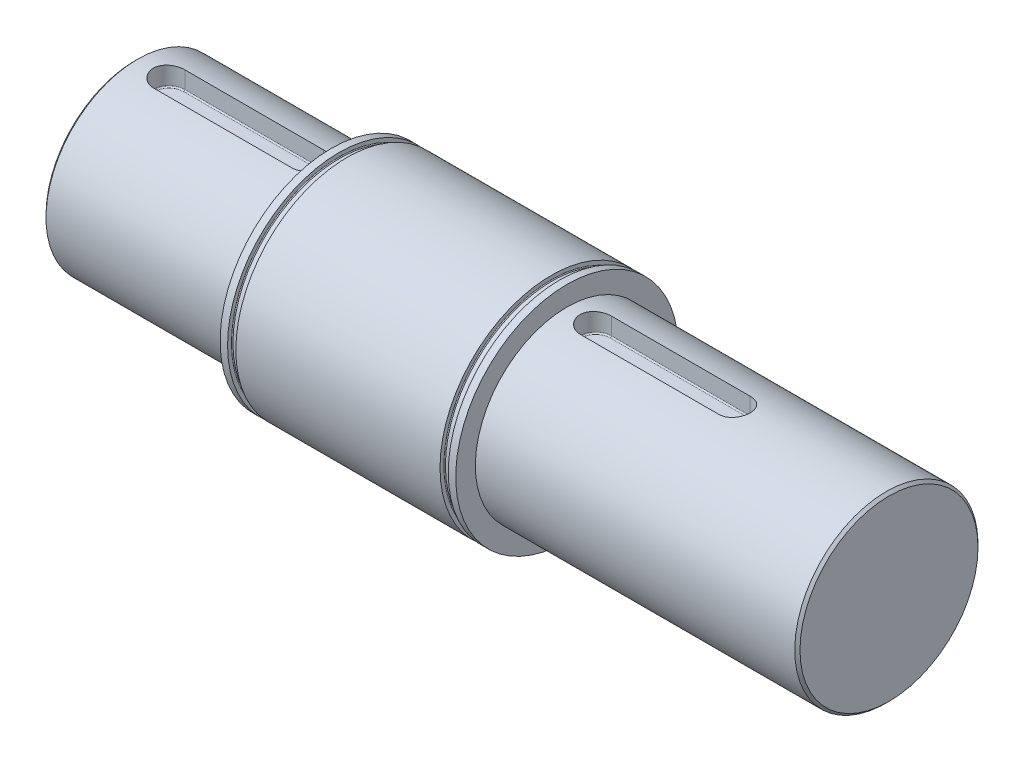
SolidWorks part; units mm, degrees
ref_plane "Front Plane" through (0, 0, 0) normal (0, 0, 1) x (1, 0, 0)
ref_plane "Top Plane" through (0, 0, 0) normal (0, 1, 0) x (1, 0, 0)
ref_plane "Right Plane" through (0, 0, 0) normal (1, 0, 0) x (0, 0, -1)
sketch "Sketch1" plane through (0, 0, 0) normal (0, 0, 1) x (1, 0, 0)
  line L0 (144, 0) -> (-144, 0) construction
  line L5 (144, 0) -> (144, 35)
  line L6 (144, 35) -> (21, 35)
  line L7 (21, 35) -> (21, 42.5)
  line L8 (21, 42.5) -> (-69, 42.5)
  line L12 (-144, 0) -> (144, 0)
  line L13 (-69, 42.5) -> (-69, 35)
  line L14 (-69, 35) -> (-144, 35)
  line L15 (-144, 35) -> (-144, 0)
  point P4 (0, 0)
  dimension "D1" = 123
  dimension "D2" = 90
  dimension "D3" = 35
  dimension "D4" = 42.5
  dimension "D5" = 75
revolve "Revolve1" add sketch "Sketch1" angle 360 about L0
sketch "Sketch3" plane through (0, 0, 0) normal (0, 0, 1) x (1, 0, 0)
  line L6 (9.2715, 0) -> (23.2848, 0) construction
  line L15 (21, 42.5) -> (-69, 42.5) construction
  line L16 (-66.15, 42.5) -> (-63, 42.5)
  line L17 (-66.15, 42.5) -> (-66.15, 40.75)
  line L18 (-66.15, 40.75) -> (-63, 40.75)
  line L19 (-63, 42.5) -> (-63, 40.75)
  line L20 (15, 42.5) -> (18.15, 42.5)
  line L21 (15, 42.5) -> (15, 40.75)
  line L22 (15, 40.75) -> (18.15, 40.75)
  line L23 (18.15, 42.5) -> (18.15, 40.75)
  line L24 (-69, 42.5) -> (-69, -42.5) construction
  line L25 (-66.15, 40.75) -> (-69, 40.75) construction
  line L26 (18.15, 40.75) -> (21, 40.75) construction
  line L27 (21, -42.5) -> (21, 42.5) construction
  dimension "D1" = 3.15
  dimension "D2" = 1.75
  dimension "D3" = 78
revolve "Cut-Revolve4" cut sketch "Sketch3" angle 360 about L6
fillet "Fillet1" radius 0.3 4 edges at (15, 0, 40.75) (18.15, 0, 40.75) (-66.15, 0, 40.75) (-63, 0, 40.75)
chamfer "Chamfer1" distance 1 angle 45 2 edges at (144, 35, 0) (-144, 35, 0)
sketch "Sketch4" plane through (0, 0, 0) normal (0, 1, 0) x (1, 0, 0)
  line L0 (21, -42.5) -> (21, 42.5) construction
  line L1 (32, 6) -> (85, 6)
  line L3 (32, -6) -> (85, -6)
  line L5 (-131, 6) -> (-78, 6)
  line L7 (-131, -6) -> (-78, -6)
  line L10 (-69, 35) -> (-69, -35) construction
  arc A0 (-131, 6) -> (-131, -6) centre (-131, 0) ccw
  arc A1 (-78, 6) -> (-78, -6) centre (-78, 0) cw
  arc A2 (85, 6) -> (85, -6) centre (85, 0) cw
  arc A3 (32, 6) -> (32, -6) centre (32, 0) ccw
  point P12 (-72, 0)
  point P13 (-137, 0)
  point P14 (91, 0)
  point P15 (26, 0)
  dimension "D1" = 53
  dimension "D2" = 53
  dimension "D3" = 12
  dimension "D4" = 12
  dimension "D5" = 5
  dimension "D6" = 3
extrude "Cut-Extrude1" cut sketch "Sketch4" along normal up to surface (6.9819 mm away) from offset 27.5
fillet "Fillet2" radius 0.5 8 edges at (58.5, 27.5, -6) (91, 27.5, 0) (58.5, 27.5, 6) (26, 27.5, 0) (-104.5, 27.5, -6) (-72, 27.5, 0) (-104.5, 27.5, 6) (-137, 27.5, 0)
